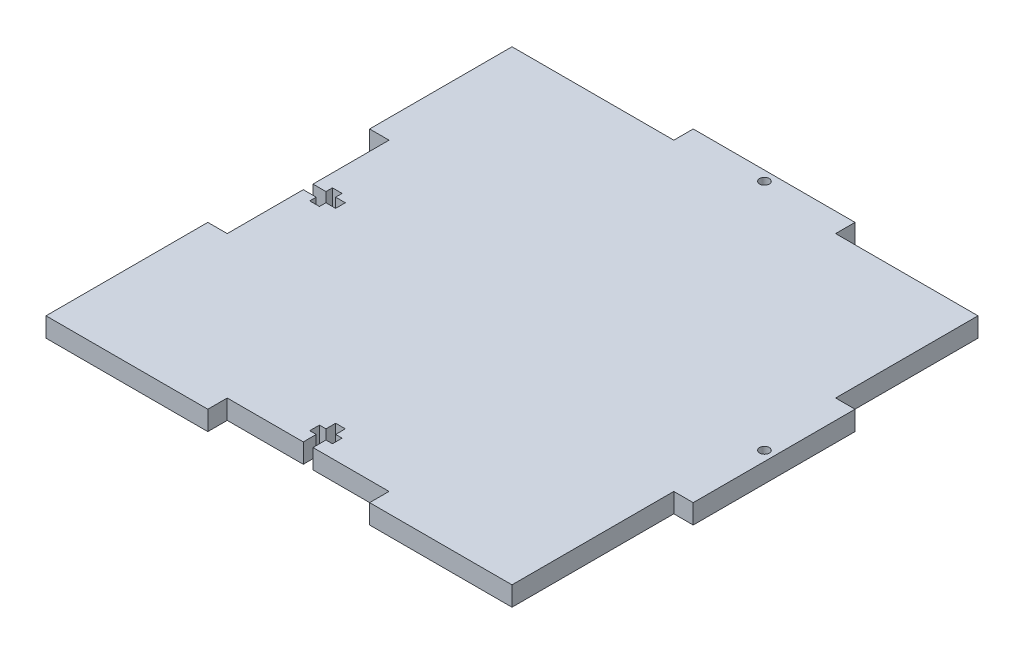
SolidWorks part; units mm, degrees
material "Acrylic (Medium-high impact)"
ref_plane "Front Plane" through (0, 0, 0) normal (0, 0, 1) x (1, 0, 0)
ref_plane "Top Plane" through (0, 0, 0) normal (0, 1, 0) x (1, 0, 0)
ref_plane "Right Plane" through (0, 0, 0) normal (1, 0, 0) x (0, 0, -1)
sketch "Sketch1" plane through (0, 0, 0) normal (0, 1, 0) x (1, 0, 0)
  line L0 (-72, 28) -> (-66, 28)
  line L1 (-72, -72) -> (72, -72)
  line L2 (-72, -72) -> (-72, 72)
  line L3 (-72, 72) -> (72, 72)
  line L4 (72, -72) -> (72, 72)
  line L5 (-72, -72) -> (72, 72) construction
  line L6 (-72, 72) -> (72, -72) construction
  line L7 (-66, 28) -> (-66, -22)
  line L8 (28, -72) -> (28, -66)
  line L9 (-22, 72) -> (-22, 78)
  line L10 (-22, 78) -> (28, 78)
  line L11 (28, 72) -> (28, 78)
  line L12 (72, 28) -> (78, 28)
  line L13 (78, 28) -> (78, -22)
  line L14 (-22, -72) -> (-22, -66)
  line L15 (-22, -66) -> (28, -66)
  line L16 (3, 78) -> (3, -72) construction
  line L17 (-72, 3) -> (78, 3) construction
  line L18 (72, -22) -> (78, -22)
  line L19 (-72, -22) -> (-66, -22)
  line L20 (75, 28) -> (75, -22) construction
  line L21 (4.5, -66) -> (4.5, -62)
  line L22 (4.5, -62) -> (6.5, -62)
  line L23 (6.5, -62) -> (6.5, -59)
  line L24 (6.5, -59) -> (4.5, -59)
  line L25 (4.5, -59) -> (4.5, -56)
  line L26 (4.5, -56) -> (1.5, -56)
  line L27 (1.5, -66) -> (1.5, -62)
  line L28 (1.5, -62) -> (-0.5, -62)
  line L29 (-0.5, -59) -> (1.5, -59)
  line L30 (-0.5, -62) -> (-0.5, -59)
  line L31 (1.5, -59) -> (1.5, -56)
  line L32 (-59, 4.5) -> (-56, 4.5)
  line L33 (-62, 4.5) -> (-62, 6.5)
  line L34 (-59, 6.5) -> (-59, 4.5)
  line L35 (-62, 6.5) -> (-59, 6.5)
  line L36 (-66, 4.5) -> (-62, 4.5)
  line L37 (-66, 1.5) -> (-62, 1.5)
  line L38 (-62, 1.5) -> (-62, -0.5)
  line L39 (-62, -0.5) -> (-59, -0.5)
  line L40 (-59, -0.5) -> (-59, 1.5)
  line L41 (-59, 1.5) -> (-56, 1.5)
  line L42 (-56, 4.5) -> (-56, 1.5)
  circle A0 centre (75, 3) radius 1.5
  circle A1 centre (3, 75) radius 1.5
  point P0 (0, 0)
  point P22 (3, 3)
  point P27 (3, 3)
  point P40 (3, -66)
  point P45 (-66, 3)
  point P49 (3, -56)
  dimension "D4" = 3
  dimension "D1" = 144
  dimension "D2" = 25
  dimension "D3" = 6
  dimension "D5" = 4
  dimension "D6" = 2
  dimension "D7" = 3
  dimension "D8" = 1.5
extrude "Boss-Extrude1" add sketch "Sketch1" along normal blind 6 contours L19 L2 L1 L14 L15 L8 L4 L3 L0 L7 | L3 L11 L10 L9 | L4 L18 L13 L12
